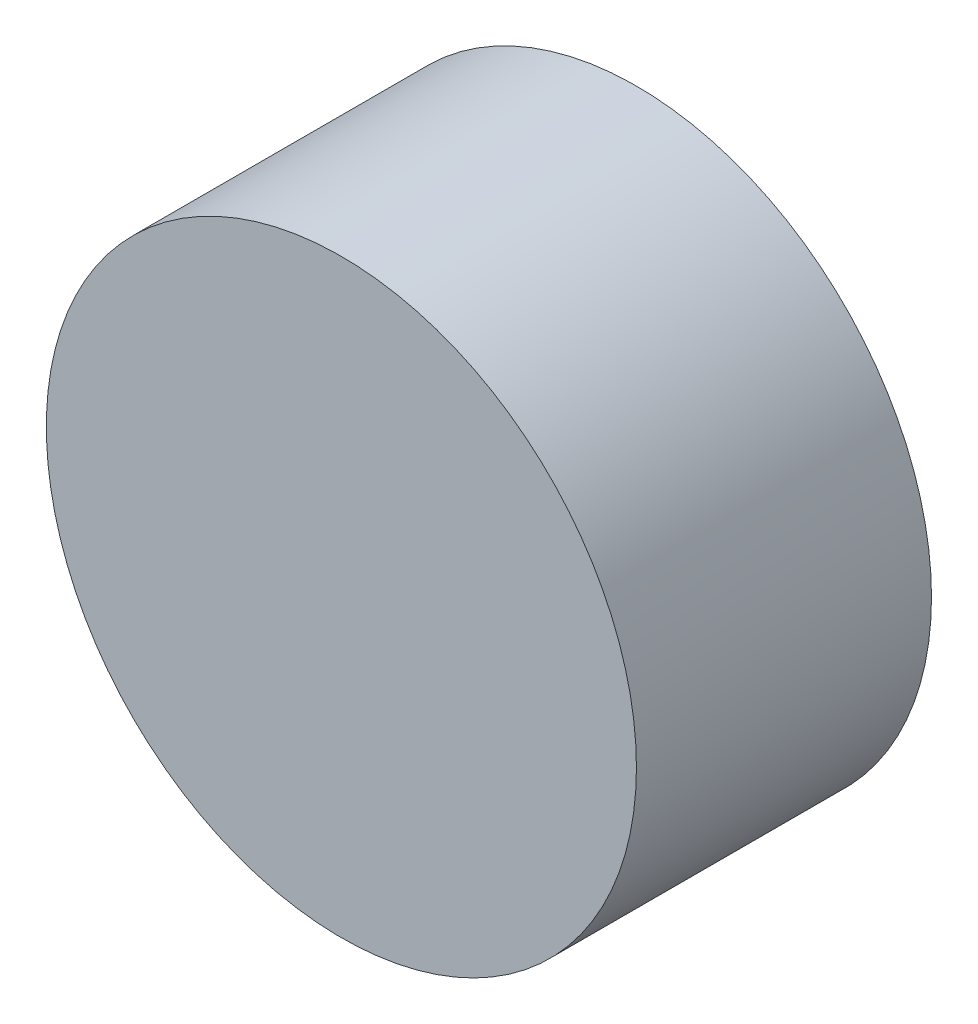
SolidWorks part; units mm, degrees
ref_plane "Front Plane" through (0, 0, 0) normal (0, 0, 1) x (1, 0, 0)
ref_plane "Top Plane" through (0, 0, 0) normal (0, 1, 0) x (1, 0, 0)
ref_plane "Right Plane" through (0, 0, 0) normal (1, 0, 0) x (0, 0, -1)
sketch "Sketch1" plane through (0, 0, 0) normal (0, 0, 1) x (1, 0, 0)
  circle A0 centre (0, 0) radius 2.5
  dimension "D1" = 5
extrude "Boss-Extrude1" add sketch "Sketch1" along normal blind 2.5
